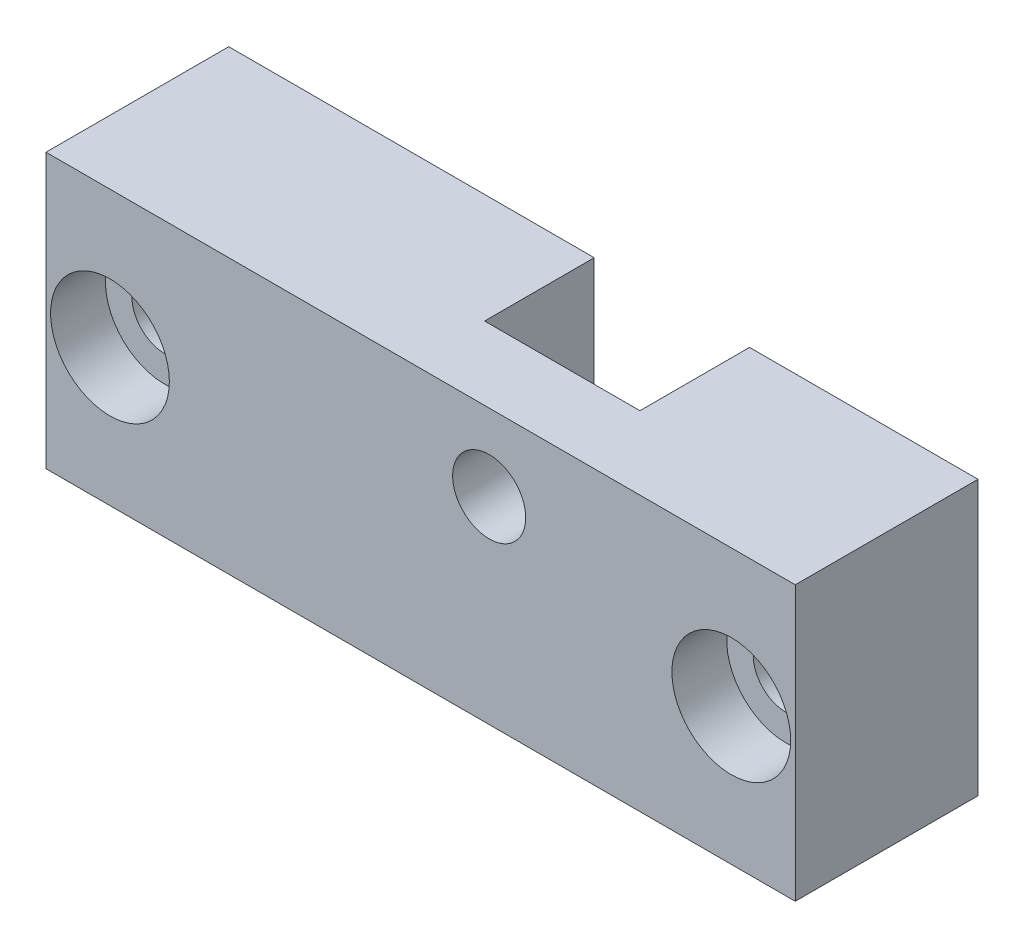
SolidWorks part; units mm, degrees
material "SKD11淬火HRC56-60"
ref_plane "前基準面" through (0, 0, 0) normal (0, 0, 1) x (1, 0, 0)
ref_plane "上基準面" through (0, 0, 0) normal (0, 1, 0) x (1, 0, 0)
ref_plane "右基準面" through (0, 0, 0) normal (1, 0, 0) x (0, 0, -1)
sketch "草图1" plane through (0, 0, 0) normal (0, 0, 1) x (1, 0, 0)
  line L1 (0, 0) -> (41, 0)
  line L2 (0, 0) -> (0, 15)
  line L3 (0, 15) -> (41, 15)
  line L4 (41, 0) -> (41, 15)
  dimension "D1" = 41
  dimension "D2" = 15
extrude "凸台-拉伸1" add sketch "草图1" along normal blind 10
hole_wizard "M3 六角凹头螺钉的柱形沉头孔1" positions "草图3" profile "草图2" counterbore size "M3" standard "ISO" end condition through all
sketch "草图3" plane through (0, 0, 10) normal (0, 0, 1) x (1, 0, 0)
  line L0 (20.5, 15) -> (20.5, 0) construction
  line L1 (41, 15) -> (0, 15) construction
  line L2 (0, 0) -> (41, 0) construction
  line L3 (0, 7.5) -> (41, 7.5) construction
  line L4 (0, 15) -> (0, 0) construction
  line L5 (41, 0) -> (41, 15) construction
  point P0 (3.5, 7.5)
  point P1 (37.5, 7.5)
  dimension "D1" = 34
sketch "草图2" plane through (3.5, 7.5, 10) normal (1, 0, 0) x (0, -1, 0)
  line L0 (0, 0) -> (0, 10)
  line L1 (0, 10) -> (1.8, 10)
  line L3 (1.8, 10) -> (1.8, 3)
  line L4 (1.8, 3) -> (3.25, 3)
  line L5 (3.25, 3) -> (3.25, 0)
  line L7 (3.25, 0) -> (0, 0)
  line L11 (0, -6.35) -> (0, 107.95) construction
  dimension "通孔孔直径" = 3.6
  dimension "通孔孔深度" = 10
  dimension "柱形沉头孔直径" = 6.5
  dimension "柱形沉头孔深度" = 3
sketch "草图4" plane through (0, 15, 0) normal (0, 1, 0) x (1, 0, 0)
  line L0 (41, 0) -> (0, 0) construction
  line L1 (20, 0) -> (28.5, 0)
  line L2 (20, 0) -> (20, -6)
  line L3 (20, -6) -> (28.5, -6)
  line L4 (28.5, 0) -> (28.5, -6)
  line L5 (0, -10) -> (0, 0) construction
  dimension "D1" = 8.5
  dimension "D2" = 6
  dimension "D3" = 20
extrude "切除-拉伸1" cut sketch "草图4" against normal through all
sketch "草图5" plane through (0, 0, 6) normal (0, 0, -1) x (-1, 0, 0)
  line L0 (-24.25, 15) -> (-24.25, 0) construction
  line L1 (-20, 15) -> (-28.5, 15) construction
  line L2 (-20, 0) -> (-28.5, 0) construction
  circle A0 centre (-24.25, 10.8) radius 2
  dimension "D1" = 4
  dimension "D2" = 4.2
extrude "切除-拉伸2" cut sketch "草图5" against normal blind 10
